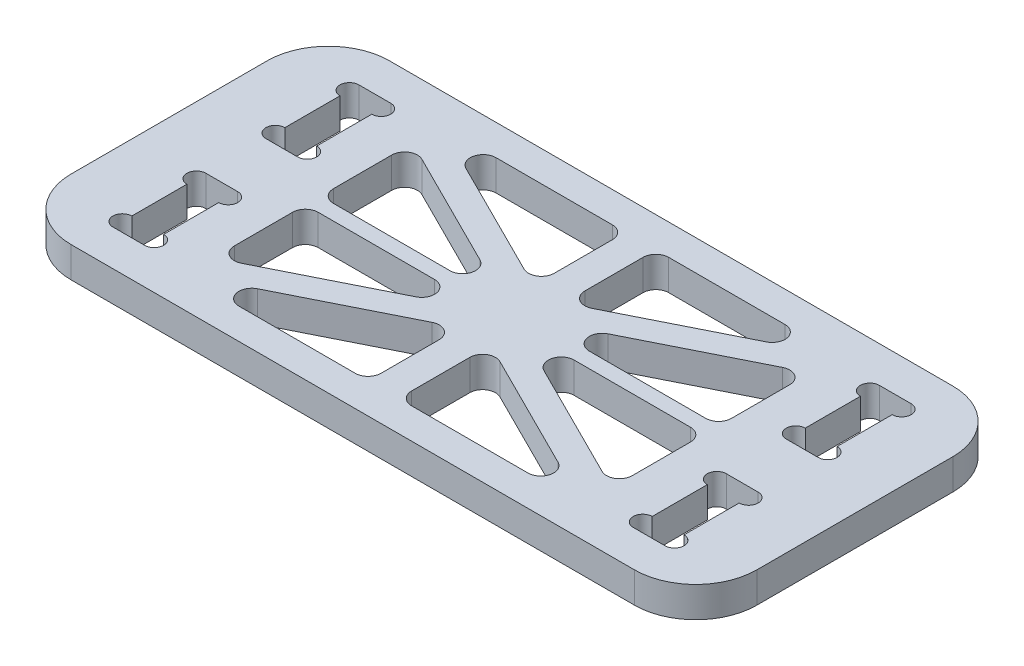
SolidWorks part; units mm, degrees
material "6061 合金"
ref_plane "前视基准面" through (0, 0, 0) normal (0, 0, 1) x (1, 0, 0)
ref_plane "上视基准面" through (0, 0, 0) normal (0, 1, 0) x (1, 0, 0)
ref_plane "右视基准面" through (0, 0, 0) normal (1, 0, 0) x (0, 0, -1)
other "Configuration Table"
sketch "草图1" plane through (0, 0, 0) normal (0, 1, 0) x (1, 0, 0)
  line L0 (0, 140.7121) -> (0, -152.4768) construction
  line L1 (-56, 26) -> (56, 26)
  line L2 (-56, 26) -> (-56, -26)
  line L3 (-56, -26) -> (56, -26)
  line L4 (56, 26) -> (56, -26)
  line L5 (-152.0124, 0) -> (209.2879, 0) construction
  line L6 (40, -5) -> (45, -5)
  line L7 (40, 20) -> (45, 20)
  line L8 (40, 20) -> (40, 5)
  line L9 (40, 5) -> (45, 5)
  line L10 (45, 20) -> (45, 5)
  line L15 (45, -20) -> (45, -5)
  line L16 (40, -20) -> (45, -20)
  line L17 (40, -20) -> (40, -5)
  line L18 (-40, -20) -> (-40, -5)
  line L19 (-40, -20) -> (-45, -20)
  line L20 (-45, -20) -> (-45, -5)
  line L21 (-40, -5) -> (-45, -5)
  line L22 (-40, 5) -> (-45, 5)
  line L23 (-45, 20) -> (-45, 5)
  line L24 (-40, 20) -> (-45, 20)
  line L25 (-40, 20) -> (-40, 5)
  dimension "D1" = 112
  dimension "D2" = 52
  dimension "D3" = 5
  dimension "D4" = 5
  dimension "D5" = 45
  dimension "D6" = 15
extrude "凸台-拉伸1" add sketch "草图1" along normal blind 5 contours L1 L4 L3 L2
other "移动面1" face at (-45, 2.5, -12.5) face at (-42.5, 2.5, -20) face at (-45, 2.5, 12.5) face at (-42.5, 2.5, 5) face at (-42.5, 2.5, 20) face at (-40, 2.5, 12.5) face at (-42.5, 2.5, -5) face at (-40, 2.5, -12.5) face at (42.5, 2.5, 20) face at (40, 2.5, 12.5) face at (45, 2.5, 12.5) face at (42.5, 2.5, 5) face at (42.5, 2.5, -5) face at (40, 2.5, -12.5) face at (42.5, 2.5, -20) face at (45, 2.5, -12.5) parameters "D1"=0.1
sketch "草图2" plane through (0, 5, 0) normal (0, 1, 0) x (1, 0, 0)
  line L0 (45.1, 4.9) -> (45.1, 20.1) construction
  line L1 (0, 0) -> (0, 45.2907) construction
  line L2 (42.5, 40.4409) -> (42.5, -36.2744) construction
  line L3 (45.1, -20.1) -> (45.1, -4.9) construction
  line L4 (39.9, -4.9) -> (39.9, -20.1) construction
  line L5 (45.1, 20.1) -> (39.9, 20.1) construction
  line L6 (39.9, 4.9) -> (45.1, 4.9) construction
  line L7 (45.1, -4.9) -> (39.9, -4.9) construction
  line L8 (39.9, -20.1) -> (45.1, -20.1) construction
  circle A0 centre (45.1, 18.55) radius 1.55
  circle A1 centre (45.1, 6.45) radius 1.55
  circle A2 centre (45.1, -6.45) radius 1.55
  circle A3 centre (45.1, -18.55) radius 1.55
  circle A4 centre (39.9, -18.55) radius 1.55
  circle A5 centre (39.9, -6.45) radius 1.55
  circle A6 centre (39.9, 6.45) radius 1.55
  circle A7 centre (39.9, 18.55) radius 1.55
  circle A8 centre (-39.9, 18.55) radius 1.55
  circle A9 centre (-39.9, 6.45) radius 1.55
  circle A10 centre (-39.9, -6.45) radius 1.55
  circle A11 centre (-39.9, -18.55) radius 1.55
  circle A12 centre (-45.1, -18.55) radius 1.55
  circle A13 centre (-45.1, -6.45) radius 1.55
  circle A14 centre (-45.1, 6.45) radius 1.55
  circle A15 centre (-45.1, 18.55) radius 1.55
  dimension "D1" = 3.1
extrude "切除-拉伸1" cut sketch "草图2" against normal blind 5
sketch "草图3" plane through (0, 5, 0) normal (0, 1, 0) x (1, 0, 0)
  line L0 (0, 0) -> (66.8883, 0) construction
  line L1 (0, 0) -> (0, 40.2589) construction
  line L2 (2.5, 21) -> (32.5, 21)
  line L3 (32.5, 21) -> (2.5, 6)
  line L4 (2.5, 6) -> (2.5, 21)
  line L5 (32.5, 16.25) -> (2.5, 1.25)
  line L6 (2.5, 1.25) -> (32.5, 1.25)
  line L7 (32.5, 1.25) -> (32.5, 16.25)
  line L8 (56, 26) -> (-56, 26) construction
  line L9 (-2.5, 1.25) -> (-32.5, 1.25)
  line L10 (-32.5, 16.25) -> (-2.5, 1.25)
  line L11 (-32.5, 1.25) -> (-32.5, 16.25)
  line L12 (-32.5, 21) -> (-2.5, 6)
  line L13 (-2.5, 21) -> (-32.5, 21)
  line L14 (-2.5, 6) -> (-2.5, 21)
  line L15 (2.5, -1.25) -> (32.5, -1.25)
  line L16 (32.5, -16.25) -> (2.5, -1.25)
  line L17 (32.5, -1.25) -> (32.5, -16.25)
  line L18 (32.5, -21) -> (2.5, -6)
  line L19 (2.5, -21) -> (32.5, -21)
  line L20 (2.5, -6) -> (2.5, -21)
  line L21 (-32.5, -1.25) -> (-32.5, -16.25)
  line L22 (-32.5, -16.25) -> (-2.5, -1.25)
  line L23 (-2.5, -1.25) -> (-32.5, -1.25)
  line L24 (-2.5, -21) -> (-32.5, -21)
  line L25 (-2.5, -6) -> (-2.5, -21)
  line L26 (-32.5, -21) -> (-2.5, -6)
  point P9 (14.5, 14.8517)
  point P13 (0, 0)
  point P14 (0, 0)
  point P15 (32.5, 13.9628)
  point P16 (2.5, 8.111)
  point P17 (32.5, 12.4073)
  point P18 (32.5, -14.2591)
  point P19 (32.5, -18.7035)
  point P38 (32.5, -21)
  dimension "D1" = 2.5
  dimension "D2" = 30
  dimension "D3" = 15
  dimension "D4" = 2.5
  dimension "D7" = 5
extrude "切除-拉伸2" cut sketch "草图3" against normal blind 5
fillet "圆角1" radius 2.1 24 edges at (-32.5, 2.5, 1.25) (-32.5, 2.5, 16.25) (-2.5, 2.5, 1.25) (2.5, 2.5, 1.25) (32.5, 2.5, 16.25) (32.5, 2.5, 1.25) (32.5, 2.5, -1.25) (2.5, 2.5, -1.25) (32.5, 2.5, -16.25) (32.5, 2.5, -21) (2.5, 2.5, -6) (2.5, 2.5, -21) (-2.5, 2.5, -21) (-2.5, 2.5, -6) (-2.5, 2.5, -1.25) (-32.5, 2.5, -1.25) (-32.5, 2.5, -16.25) (-32.5, 2.5, -21) (32.5, 2.5, 21) (2.5, 2.5, 6) (2.5, 2.5, 21) (-2.5, 2.5, 21) (-2.5, 2.5, 6) (-32.5, 2.5, 21)
fillet "圆角2" radius 10 4 edges at (-56, 2.5, 26) (-56, 2.5, -26) (56, 2.5, -26) (56, 2.5, 26)
